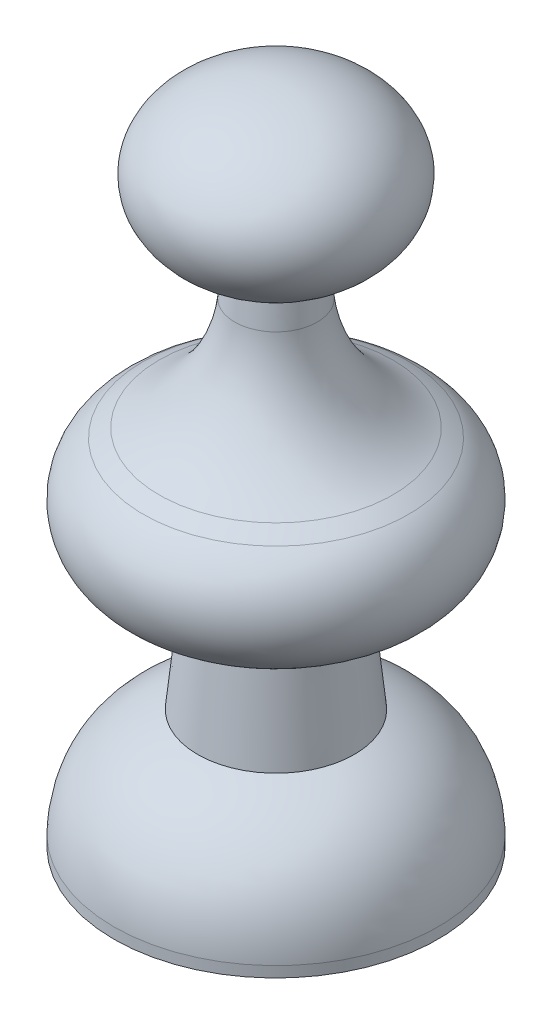
SolidWorks part; units mm, degrees
ref_plane "Front Plane" through (0, 0, 0) normal (0, 0, 1) x (1, 0, 0)
ref_plane "Top Plane" through (0, 0, 0) normal (0, 1, 0) x (1, 0, 0)
ref_plane "Right Plane" through (0, 0, 0) normal (1, 0, 0) x (0, 0, -1)
sketch "Sketch1" plane through (0, 0, 0) normal (0, 0, 1) x (1, 0, 0)
  line L0 (0, 0) -> (0, 46.0375) construction
  line L1 (0, 0) -> (-11.5, 0)
  line L2 (-5.5562, 7.6173) -> (-4.9017, 13.9035)
  line L3 (0, 26.9875) -> (-33.3364, 26.9875) construction
  line L4 (-11.5, 0) -> (-11.5, 46.0375) construction
  line L5 (-3.5771, 26.6242) -> (-2.6788, 35.251)
  line L6 (0, 46.0375) -> (0, 0)
  arc A0 (-3.5771, 26.6242) -> (-9.4101, 24.295) centre (0, 9.1974) ccw
  arc A1 (-9.4101, 24.295) -> (-8.6822, 16.399) centre (-7.0633, 20.5298) ccw
  arc A2 (-8.6822, 16.399) -> (-6.0312, 15.5356) centre (0, 38.5535) ccw
  arc A3 (-4.9017, 13.9035) -> (-6.0312, 15.5356) centre (-6.4175, 14.0613) ccw
  ellipse E0 centre (0, 40.4813) end of major axis (7.9375, 40.4813) minor radius 5.5562 (0, 46.0375) -> (-2.6788, 35.251) ccw
  spline S0 degree 2 poles (-11.5, 0) (-11.2207, 5.5448) (-5.5562, 7.6173) knots 0 0 0 1 1 1
  point P16 (-4.7625, 15.24)
  dimension "D10" = 1.524
  dimension "D1" = 46.0375
  dimension "D2" = 23
  dimension "D3" = 9.525
  dimension "D4" = 11.1125
  dimension "D5" = 7.6173
  dimension "D6" = 3.5818
  dimension "D7" = 10.5804
  dimension "D8" = 15.24
  dimension "D9" = 26.9875
  dimension "D11" = 15.875
  dimension "D12" = 11.1125
revolve "Revolve2" add sketch "Sketch1" angle 360 about L6
fillet "Fillet1" radius 10.16 1 edges at (0, 26.6242, 3.5771)
sketch "Sketch2" plane through (0, 0, 0) normal (0, -1, 0) x (1, 0, 0)
  circle A1 centre (0, 0) radius 11.5
  circle A2 centre (0, 0) radius 11.5
  dimension "D1" = 0
extrude "Boss-Extrude1" add sketch "Sketch2" along normal blind 0.762 separate body
